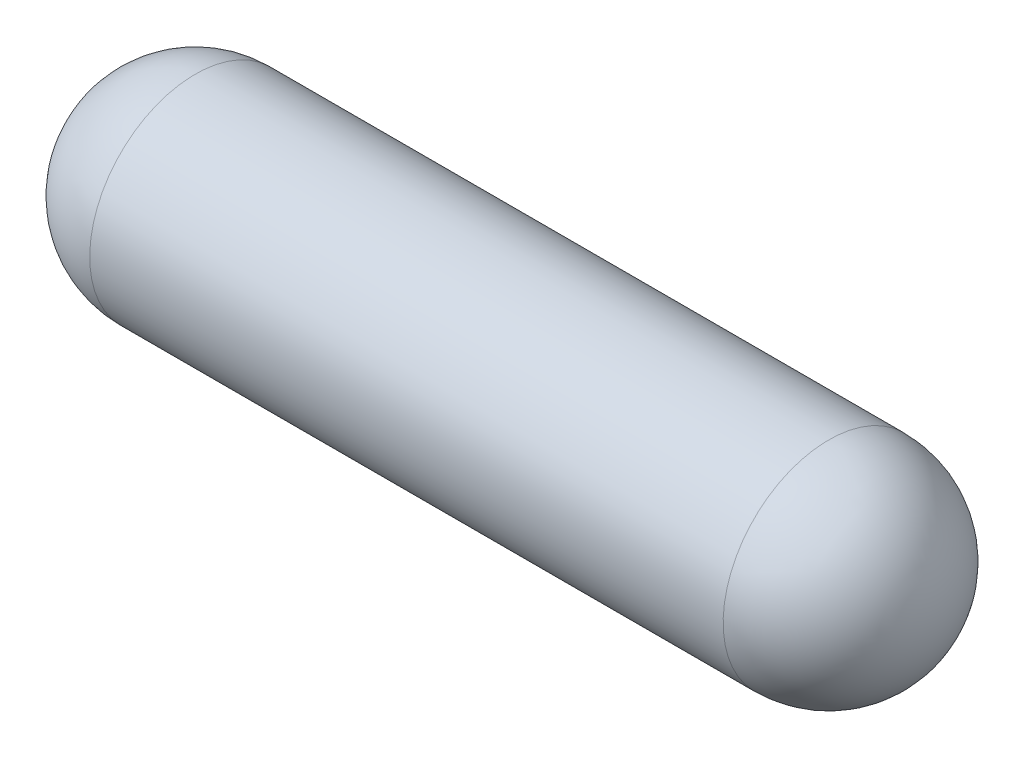
SolidWorks part; units mm, degrees
ref_plane "Front" through (0, 0, 0) normal (0, 0, 1) x (1, 0, 0)
ref_plane "Top" through (0, 0, 0) normal (0, 1, 0) x (1, 0, 0)
ref_plane "Right" through (0, 0, 0) normal (1, 0, 0) x (0, 0, -1)
sketch "Sketch1" plane through (0, 0, 0) normal (0, 0, 1) x (1, 0, 0)
  line L0 (0, 0) -> (38.1, 0)
  line L1 (44.45, 6.35) -> (-6.35, 6.35)
  line L2 (-6.35, 6.35) -> (-6.35, 0) construction
  line L3 (-6.35, 0) -> (0, 0) construction
  line L4 (38.1, 0) -> (44.45, 0) construction
  line L5 (44.45, 0) -> (44.45, 6.35) construction
  arc A0 (38.1, 0) -> (44.45, 6.35) centre (38.1, 6.35) ccw
  arc A1 (-6.35, 6.35) -> (0, 0) centre (0, 6.35) ccw
  point P7 (41.0308, 0)
  dimension "D2" = 6.35
  dimension "D1" = 38.1
revolve "Revolve1" add sketch "Sketch1" angle 360 about L1
